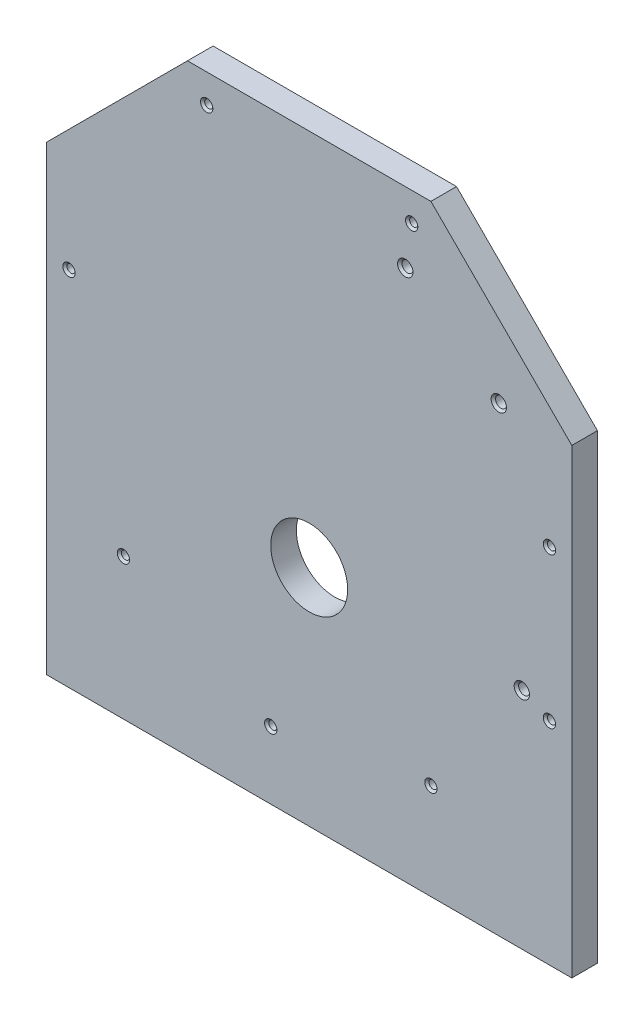
SolidWorks part; units mm, degrees
ref_plane "Front Plane" through (0, 0, 0) normal (0, 0, 1) x (1, 0, 0)
ref_plane "Top Plane" through (0, 0, 0) normal (0, 1, 0) x (1, 0, 0)
ref_plane "Right Plane" through (0, 0, 0) normal (1, 0, 0) x (0, 0, -1)
sketch "Sketch1" plane through (0, 0, 0) normal (0, 0, 1) x (1, 0, 0)
  line L0 (-130.175, -168.275) -> (130.175, -168.275)
  line L1 (130.175, -168.275) -> (130.175, 60.325)
  line L2 (130.175, 60.325) -> (60.325, 130.175)
  line L3 (60.325, 130.175) -> (-60.325, 130.175)
  line L4 (-60.325, 130.175) -> (-130.175, 60.325)
  line L5 (-130.175, 60.325) -> (-130.175, -168.275)
  point P0 (0, -168.275)
  point P2 (0, 130.175)
  dimension "D1" = 260.35
  dimension "D2" = 298.45
  dimension "D3" = 130.175
  dimension "D4" = 69.85
  dimension "D5" = 45
extrude "Boss-Extrude1" add sketch "Sketch1" along normal blind 12.7
sketch "Sketch2" plane through (0, 0, 0) normal (0, 0, 1) x (1, 0, 0)
  circle A0 centre (0, -57.15) radius 19.0754
  dimension "D2" = 38.1508
  dimension "D1" = 57.15
extrude "Cut-Extrude2" cut sketch "Sketch2" along normal through all
hole_wizard "#10-32 Tapped Hole2" positions "Sketch6" profile "Sketch5" tap size "#10-32" standard "ANSI Inch" end condition up to next
sketch "Sketch6" plane through (0, 0, 0) normal (0, 0, -1) x (-1, 0, 0)
  point P0 (-50.8, 115.8875)
  point P2 (50.8, 115.8875)
  point P4 (119.0752, 11.1252)
  point P6 (92.075, -98.425)
  point P8 (19.05, -134.9375)
  point P10 (-60.325, -120.65)
  point P12 (-119.0752, 11.1252)
  point P47 (-119.0752, -63.5)
  dimension "D1" = 50.8
  dimension "D2" = 50.8
  dimension "D3" = 115.8875
  dimension "D4" = 11.1252
  dimension "D5" = 119.0752
  dimension "D6" = 119.0752
  dimension "D7" = 120.65
  dimension "D8" = 60.325
  dimension "D9" = 98.425
  dimension "D10" = 92.075
  dimension "D11" = 19.05
  dimension "D12" = 134.9375
  dimension "D13" = 63.5
sketch "Sketch5" plane through (50.8, 115.8875, 0) normal (1, 0, 0) x (0, 1, 0)
  line L0 (0, 0) -> (0, 12.7)
  line L1 (0, 12.7) -> (3.048, 12.7)
  line L2 (2.0193, 11.6713) -> (2.0193, 1.0287)
  line L3 (2.0193, 1.0287) -> (3.048, 0)
  line L5 (3.048, 0) -> (0, 0)
  line L6 (-2.0193, 1.0287) -> (-3.048, 0) construction
  line L7 (3.048, 12.7) -> (2.0193, 11.6713)
  line L8 (-3.048, 12.7) -> (-2.0193, 11.6713) construction
  line L11 (0, -6.35) -> (0, 107.95) construction
  dimension "Thread Major Dia." = 4.0386
  dimension "Thru Tap Drill Depth" = 12.7
  dimension "Near C'Sink Dia." = 6.096
  dimension "Near C'Sink Angle" = 90
  dimension "Far C'Sink Dia." = 6.096
  dimension "Far C'Sink Angle" = 90
hole_wizard "1/4-28 Tapped Hole1" positions "Sketch8" profile "Sketch7" tap size "1/4-28" standard "ANSI Inch" end condition through all
sketch "Sketch8" plane through (0, 0, 0) normal (0, 0, -1) x (-1, 0, 0)
  point P0 (-105.41, -57.15)
  point P2 (-93.98, 60.325)
  point P4 (-47.625, 95.25)
  dimension "D1" = 105.41
  dimension "D2" = 57.15
  dimension "D3" = 60.325
  dimension "D4" = 93.98
  dimension "D5" = 95.25
  dimension "D6" = 47.625
sketch "Sketch7" plane through (105.41, -57.15, 0) normal (1, 0, 0) x (0, 1, 0)
  line L0 (0, 0) -> (0, 12.7)
  line L1 (0, 12.7) -> (3.81, 12.7)
  line L2 (2.7051, 11.5951) -> (2.7051, 1.1049)
  line L3 (2.7051, 1.1049) -> (3.81, 0)
  line L5 (3.81, 0) -> (0, 0)
  line L6 (-2.7051, 1.1049) -> (-3.81, 0) construction
  line L7 (3.81, 12.7) -> (2.7051, 11.5951)
  line L8 (-3.81, 12.7) -> (-2.7051, 11.5951) construction
  line L11 (0, -6.35) -> (0, 107.95) construction
  dimension "Thread Major Dia." = 5.4102
  dimension "Thru Tap Drill Depth" = 12.7
  dimension "Near C'Sink Dia." = 7.62
  dimension "Near C'Sink Angle" = 90
  dimension "Far C'Sink Dia." = 7.62
  dimension "Far C'Sink Angle" = 90
